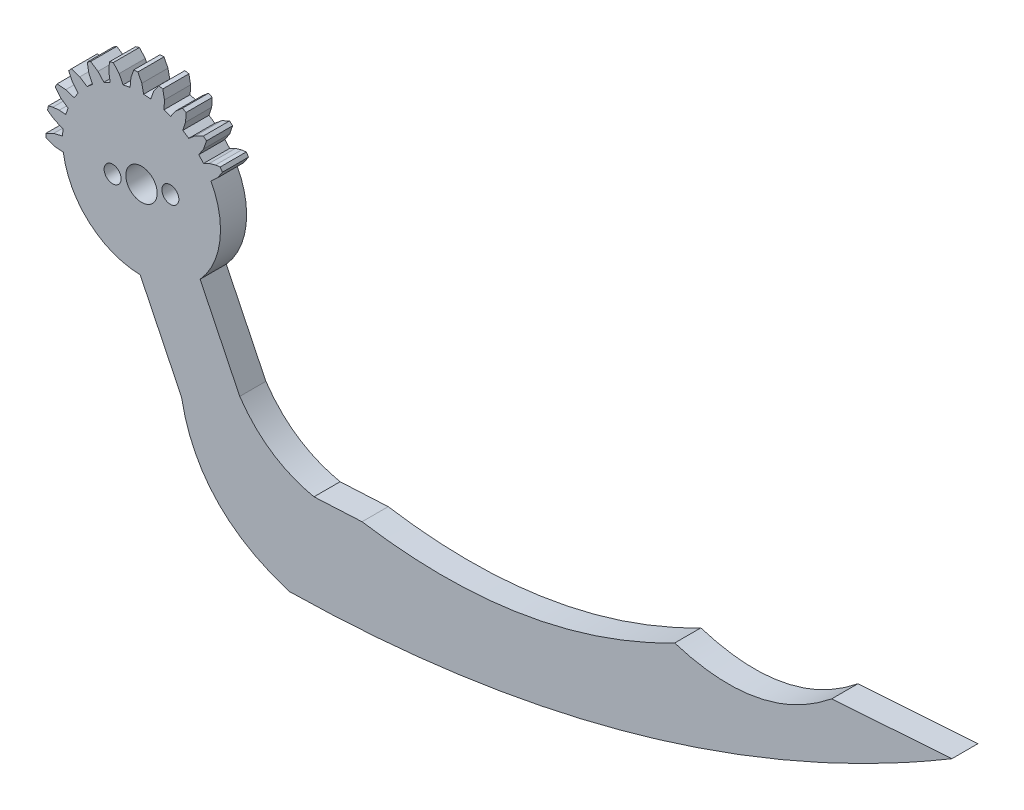
SolidWorks part; units mm, degrees
material "ABS"
ref_plane "Front Plane" through (0, 0, 0) normal (0, 0, 1) x (1, 0, 0)
ref_plane "Top Plane" through (0, 0, 0) normal (0, 1, 0) x (1, 0, 0)
ref_plane "Right Plane" through (0, 0, 0) normal (1, 0, 0) x (0, 0, -1)
sketch "Sketch1" plane through (0, 0, 0) normal (0, 0, 1) x (1, 0, 0)
  line L1 (-75, -35) -> (75, -35)
  line L2 (-75, -35) -> (-75, 35)
  line L3 (-75, 35) -> (75, 35)
  line L4 (75, -35) -> (75, 35)
  line L5 (-75, -35) -> (75, 35) construction
  line L6 (-75, 35) -> (75, -35) construction
  point P0 (0, 0)
  dimension "D1" = 150
  dimension "D2" = 70
extrude "Boss-Extrude1" add sketch "Sketch1" along normal blind 4
sketch "Sketch2" plane through (0, 0, 4) normal (0, 0, 1) x (1, 0, 0)
  line L0 (49.9845, 0.6677) -> (68.3684, 1.9203)
  line L1 (-46.6879, 7.9474) -> (-40.6254, -4.5523)
  line L2 (-55.8686, 3.9611) -> (-49.5357, -9.0961)
  line L3 (-45.03, 21.8122) -> (-44.028, 22.7135)
  line L4 (-43.2805, 23.8348) -> (-44.028, 22.7135)
  line L5 (-43.2805, 23.8348) -> (-43.6238, 24.3561)
  line L6 (-43.6238, 24.3561) -> (-44.3345, 24.2679)
  line L7 (-44.3345, 24.2679) -> (-45.2869, 23.9923)
  line L8 (-45.2869, 23.9923) -> (-46.1728, 23.5472)
  line L9 (-46.1728, 23.5472) -> (-46.8831, 24.3679)
  line L10 (-46.8831, 24.3679) -> (-46.1486, 25.4978)
  line L11 (-46.1486, 25.4978) -> (-45.7167, 26.7744)
  line L12 (-45.7167, 26.7744) -> (-46.1833, 27.189)
  line L13 (-46.1833, 27.189) -> (-47.4003, 26.6101)
  line L14 (-47.4003, 26.6101) -> (-48.436, 25.748)
  line L15 (-48.436, 25.748) -> (-49.3346, 26.3569)
  line L16 (-49.3346, 26.3569) -> (-48.9175, 27.6384)
  line L17 (-48.9175, 27.6384) -> (-48.8307, 28.9833)
  line L18 (-48.8307, 28.9833) -> (-49.3887, 29.263)
  line L19 (-49.3887, 29.263) -> (-50.4144, 28.3889)
  line L20 (-50.4144, 28.3889) -> (-51.1917, 27.288)
  line L21 (-51.1917, 27.288) -> (-52.2173, 27.6436)
  line L22 (-52.2173, 27.6436) -> (-52.1461, 28.9894)
  line L23 (-52.1461, 28.9894) -> (-52.4104, 30.3109)
  line L24 (-52.4104, 30.3109) -> (-53.0217, 30.4367)
  line L25 (-53.0217, 30.4367) -> (-53.7862, 29.3269)
  line L26 (-53.7862, 29.3269) -> (-54.2521, 28.0623)
  line L27 (-54.2521, 28.0623) -> (-55.3348, 28.1404)
  line L28 (-55.3348, 28.1404) -> (-55.6143, 29.4588)
  line L29 (-55.6143, 29.4588) -> (-56.2116, 30.6668)
  line L30 (-56.2116, 30.6668) -> (-56.8347, 30.6301)
  line L31 (-56.8347, 30.6301) -> (-57.2859, 29.3602)
  line L32 (-57.2859, 29.3602) -> (-57.4087, 28.0182)
  line L33 (-57.4087, 28.0182) -> (-58.4746, 27.8134)
  line L34 (-58.4746, 27.8134) -> (-59.0859, 29.0145)
  line L35 (-59.0859, 29.0145) -> (-59.9755, 30.0268)
  line L36 (-59.9755, 30.0268) -> (-60.5678, 29.83)
  line L37 (-60.5678, 29.83) -> (-60.675, 28.4866)
  line L38 (-60.675, 28.4866) -> (-60.4462, 27.1586)
  line L39 (-60.4462, 27.1586) -> (-61.4229, 26.6849)
  line L40 (-61.4229, 26.6849) -> (-62.3241, 27.6868)
  line L41 (-62.3241, 27.6868) -> (-63.4454, 28.4344)
  line L42 (-63.4454, 28.4344) -> (-63.9667, 28.091)
  line L43 (-63.9667, 28.091) -> (-63.7225, 26.7657)
  line L44 (-63.7225, 26.7657) -> (-63.1578, 25.5421)
  line L45 (-63.1578, 25.5421) -> (-63.9786, 24.8318)
  line L46 (-63.9786, 24.8318) -> (-65.1084, 25.5663)
  line L47 (-65.1084, 25.5663) -> (-66.385, 25.9982)
  line L48 (-66.385, 25.9982) -> (-66.7996, 25.5316)
  line L49 (-66.7996, 25.5316) -> (-66.2208, 24.3146)
  line L50 (-66.2208, 24.3146) -> (-65.3586, 23.2788)
  line L51 (-65.3586, 23.2788) -> (-65.9675, 22.3803)
  line L52 (-65.9675, 22.3803) -> (-67.249, 22.7974)
  line L53 (-67.249, 22.7974) -> (-68.5939, 22.8841)
  line L54 (-68.5939, 22.8841) -> (-68.8736, 22.3261)
  line L55 (-68.8736, 22.3261) -> (-67.9995, 21.3004)
  line L56 (-67.9995, 21.3004) -> (-66.8986, 20.5231)
  line L57 (-66.8986, 20.5231) -> (-67.2543, 19.4976)
  line L58 (-67.2543, 19.4976) -> (-68.2421, 19.5828)
  line L59 (-68.2421, 19.5828) -> (-69.2288, 19.4859)
  line L60 (-69.2288, 19.4859) -> (-69.9215, 19.3045)
  line L61 (-69.9215, 19.3045) -> (-70.0473, 18.6931)
  line L62 (-70.0473, 18.6931) -> (-69.2628, 18.1118)
  line L63 (-69.2628, 18.1118) -> (-68.3865, 17.6811)
  line L64 (-68.3865, 17.6811) -> (-67.679, 17.4098)
  line L65 (-67.679, 17.4098) -> (-67.751, 16.3801)
  line L66 (-67.751, 16.3801) -> (-69.0694, 16.1005)
  line L67 (-69.0694, 16.1005) -> (-70.2774, 15.5032)
  line L68 (-70.2774, 15.5032) -> (-70.2407, 14.8802)
  line L69 (-70.2407, 14.8802) -> (-68.9708, 14.4289)
  line L70 (-68.9708, 14.4289) -> (-67.6288, 14.3062)
  line L71 (-29.2633, -12.1781) -> (-21.9053, -11.8027)
  arc A0 (-45.03, 21.8122) -> (-43.2805, 23.8348) centre (-48.1122, 26.2462) ccw construction
  arc A1 (-44.3345, 24.2679) -> (-46.1728, 23.5472) centre (-43.3158, 18.9649) ccw construction
  arc A2 (-46.8831, 24.3679) -> (-45.7167, 26.7744) centre (-51.0079, 27.8531) ccw construction
  arc A3 (-46.1833, 27.189) -> (-48.436, 25.748) centre (-44.4904, 22.0612) ccw construction
  arc A4 (-49.3346, 26.3569) -> (-48.8307, 28.9833) centre (-54.2208, 28.6558) ccw construction
  arc A5 (-48.436, 25.748) -> (-49.3346, 26.3569) centre (-55.6627, 16.0521) ccw construction
  arc A6 (-49.3887, 29.263) -> (-51.1917, 27.288) centre (-46.4264, 24.7481) ccw construction
  arc A7 (-52.2173, 27.6436) -> (-52.4104, 30.3109) centre (-57.532, 28.5995) ccw construction
  arc A8 (-53.0217, 30.4367) -> (-54.2521, 28.0623) centre (-48.9918, 26.8423) ccw construction
  arc A9 (-55.3348, 28.1404) -> (-56.2116, 30.6668) centre (-60.7158, 27.6882) ccw construction
  arc A10 (-56.8347, 30.6301) -> (-57.4087, 28.0182) centre (-52.0118, 28.2013) ccw construction
  arc A11 (-58.4746, 27.8134) -> (-59.9755, 30.0268) centre (-63.5552, 25.9838) ccw construction
  arc A12 (-60.5678, 29.83) -> (-60.4462, 27.1586) centre (-55.2806, 28.7322) ccw construction
  arc A13 (-61.4229, 26.6849) -> (-63.4454, 28.4344) centre (-65.8568, 23.6027) ccw construction
  arc A14 (-63.9667, 28.091) -> (-63.1578, 25.5421) centre (-58.5755, 28.3991) ccw construction
  arc A15 (-63.9786, 24.8318) -> (-66.385, 25.9982) centre (-67.4637, 20.707) ccw construction
  arc A16 (-66.7996, 25.5316) -> (-65.3586, 23.2788) centre (-61.6718, 27.2245) ccw construction
  arc A17 (-65.9675, 22.3803) -> (-68.5939, 22.8841) centre (-68.2664, 17.4941) ccw construction
  arc A18 (-68.8736, 22.3261) -> (-66.8986, 20.5231) centre (-64.3587, 25.2885) ccw construction
  arc A19 (-67.2543, 19.4976) -> (-69.2288, 19.4859) centre (-68.2101, 14.1829) ccw construction
  arc A20 (-70.0473, 18.6931) -> (-68.3865, 17.6811) centre (-66.453, 22.7231) ccw construction
  arc A21 (-67.751, 16.3801) -> (-70.2774, 15.5032) centre (-67.2988, 10.9991) ccw construction
  arc A22 (-70.2407, 14.8802) -> (-67.6288, 14.3062) centre (-67.8119, 19.7031) ccw construction
  arc A23 (-67.6288, 14.3062) -> (-55.8686, 3.9611) centre (-55.6627, 16.0521) ccw
  arc A24 (-67.6288, 14.3062) -> (-55.8686, 3.9611) centre (-55.6627, 16.0521) ccw construction
  arc A25 (-45.03, 21.8122) -> (-46.6879, 7.9474) centre (-55.6627, 16.0521) cw
  arc A26 (-46.6879, 7.9474) -> (-45.03, 21.8122) centre (-55.6627, 16.0521) ccw construction
  circle A27 centre (-55.6627, 16.0521) radius 2.4
  circle A28 centre (-51.2435, 16.901) radius 1.3
  circle A29 centre (-60.0819, 15.2032) radius 1.3
  spline S0 degree 3 poles (-40.6254, -4.5523) (-39.9697, -5.5186) (-38.642, -7.16) (-36.3833, -9.1193) (-34.1814, -10.4825) (-31.8147, -11.5175) (-30.1732, -11.9828) (-29.2633, -12.1781) knots 0 0 0 0 0.249608 0.449336 0.63625 0.801037 1 1 1 1
  spline S1 degree 2 poles (-40.6254, -4.5523) (-36.5037, -10.6235) (-29.2633, -12.1781) knots 0 0 0 1 1 1 weights 1 1 1 construction
  spline S2 degree 3 poles (-21.9053, -11.8027) (-20.3109, -12.0551) (-17.1699, -12.4598) (-12.4839, -12.7828) (-8.0459, -12.8224) (-3.6491, -12.6086) (1.2833, -12.0805) (5.9387, -11.2336) (10.0554, -10.2065) (13.0819, -9.3129) (16.4745, -8.1639) (20.7936, -6.4641) (24.0864, -4.9092) (25.9432, -3.9505) knots 0 0 0 0 0.098157 0.192486 0.285432 0.367866 0.460021 0.586889 0.655199 0.717944 0.778719 0.87295 1 1 1 1
  spline S3 degree 2 poles (-6.584, -12.7385) (-14.1425, -13.0315) (-21.9053, -11.8027) knots 0.605436 0.605436 0.605436 0.878376 0.878376 0.878376 weights 1 1 1 construction
  spline S4 degree 2 poles (25.9432, -3.9505) (10.2877, -12.034) (-6.3596, -12.7294) knots 0 0 0 0.601382 0.601382 0.601382 weights 1 1 1 construction
  spline S5 degree 3 poles (25.9432, -3.9505) (27.847, -4.5472) (31.2871, -5.2905) (36.7356, -5.3381) (41.1433, -4.3665) (45.7717, -2.37) (48.3781, -0.6348) (49.9845, 0.6677) knots 0 0 0 0 0.234141 0.410074 0.635495 0.757256 1 1 1 1
  spline S6 degree 2 poles (49.9845, 0.6677) (39.1674, -8.0919) (25.9432, -3.9505) knots 0 0 0 1 1 1 weights 1 1 1 construction
  spline S7 degree 3 poles (-49.5357, -9.0961) (-49.3398, -10.1379) (-48.7974, -12.328) (-47.5397, -15.4201) (-45.7072, -18.4011) (-43.5434, -20.8317) (-40.9132, -22.9741) (-37.5163, -25.0051) (-34.7071, -26.0963) (-33.005, -26.6186) knots 0 0 0 0 0.124884 0.265437 0.391415 0.535531 0.646519 0.790098 1 1 1 1
  spline S8 degree 2 poles (-49.5357, -9.0961) (-47.0518, -22.3101) (-33.005, -26.6186) knots 0 0 0 1 1 1 weights 1 1 1 construction
  spline S9 degree 3 poles (-33.005, -26.6186) (-30.2945, -26.5749) (-25.8805, -26.424) (-19.542, -26.0145) (-14.3199, -25.5434) (-8.9981, -24.9277) (-2.8901, -24.0675) (4.3644, -22.7969) (11.8702, -21.1597) (19.8279, -19.1103) (26.8845, -16.9793) (34.0376, -14.5034) (39.9364, -12.2434) (45.7825, -9.7788) (51.4234, -7.1978) (59.0098, -3.4374) (64.6825, -0.2805) (68.3684, 1.9203) knots 0 0 0 0 0.076325 0.124331 0.178824 0.223937 0.27516 0.352481 0.431247 0.491395 0.58382 0.638694 0.704497 0.76164 0.817302 0.879134 1 1 1 1
  spline S10 degree 2 poles (68.3684, 1.9203) (22.0587, -25.7298) (-33.005, -26.6186) knots 0 0 0 0.99765 0.99765 0.99765 weights 1 1 1 construction
  line M2 (75, -35) -> (75, 35)
  line M3 (75, 35) -> (-75, 35)
  line M4 (-75, 35) -> (-75, -35)
  line M5 (-75, -35) -> (75, -35)
extrude "Cut-Extrude1" cut sketch "Sketch2" against normal blind 10 contours S9 S7 L2 A23 L70 L69 L68 L67 L66 L65 L64 L63 L62 L61 L60 L59 L58 L57 L56 L55 L54 L53 L52 L51 L50 L49 L48 L47 L46 L45 L44 L43 L42 L41 L40 L39 L38 L37 L36 L35 L34 L33 L32 L31 L30 L29 M5 M2 M3 M4 | A29 | A27 | A28
